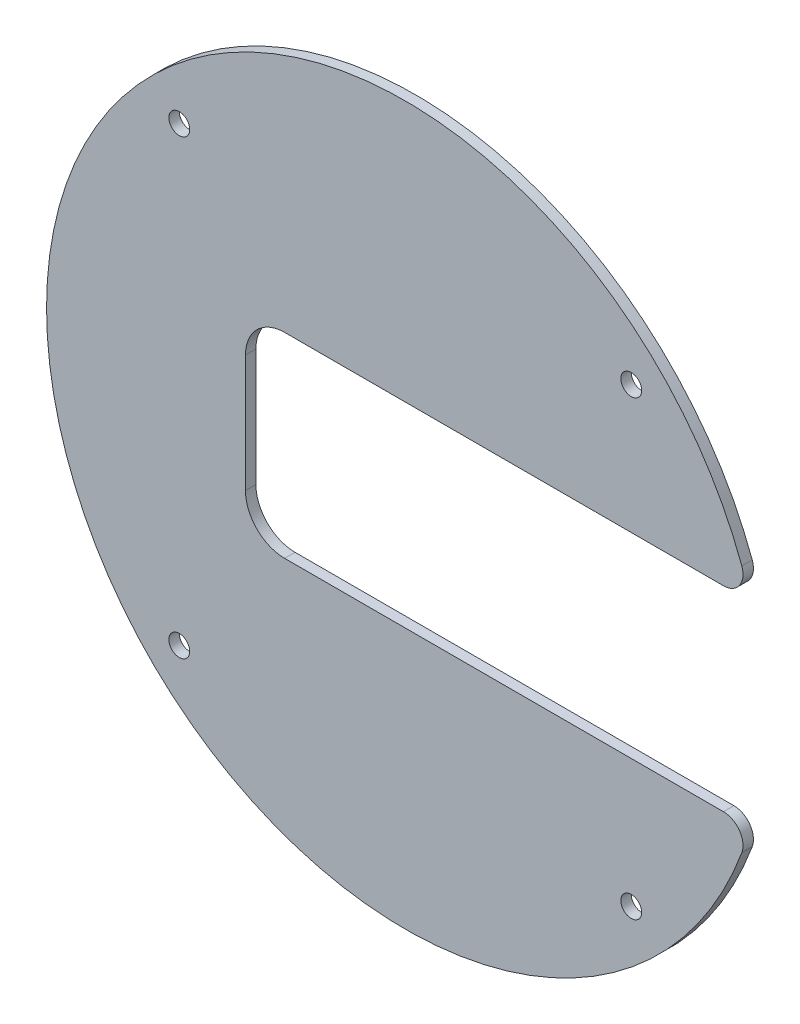
SolidWorks part; units mm, degrees
ref_plane "Front Plane" through (0, 0, 0) normal (0, 0, 1) x (1, 0, 0)
ref_plane "Top Plane" through (0, 0, 0) normal (0, 1, 0) x (1, 0, 0)
ref_plane "Right Plane" through (0, 0, 0) normal (1, 0, 0) x (0, 0, -1)
sketch "草圖1" plane through (0, 0, 0) normal (0, 0, 1) x (1, 0, 0)
  line L0 (52.915, -15) -> (-24.5, -15)
  line L1 (-24.5, -15) -> (-24.5, 15)
  line L2 (-24.5, 15) -> (52.915, 15)
  arc A0 (52.915, 15) -> (52.915, -15) centre (0, 0) ccw
  circle A1 centre (34.6482, 34.6482) radius 1.6
  circle A2 centre (-34.6482, 34.6482) radius 1.6
  circle A3 centre (-34.6482, -34.6482) radius 1.6
  circle A4 centre (34.6482, -34.6482) radius 1.6
extrude "填料-伸長1" add sketch "草圖1" along normal blind 1.6
fillet "圓角1" radius 6 2 edges at (-24.5, 15, 0.8) (-24.5, -15, 0.8)
fillet "圓角2" radius 3 2 edges at (52.915, 15, 0.8) (52.915, -15, 0.8)
